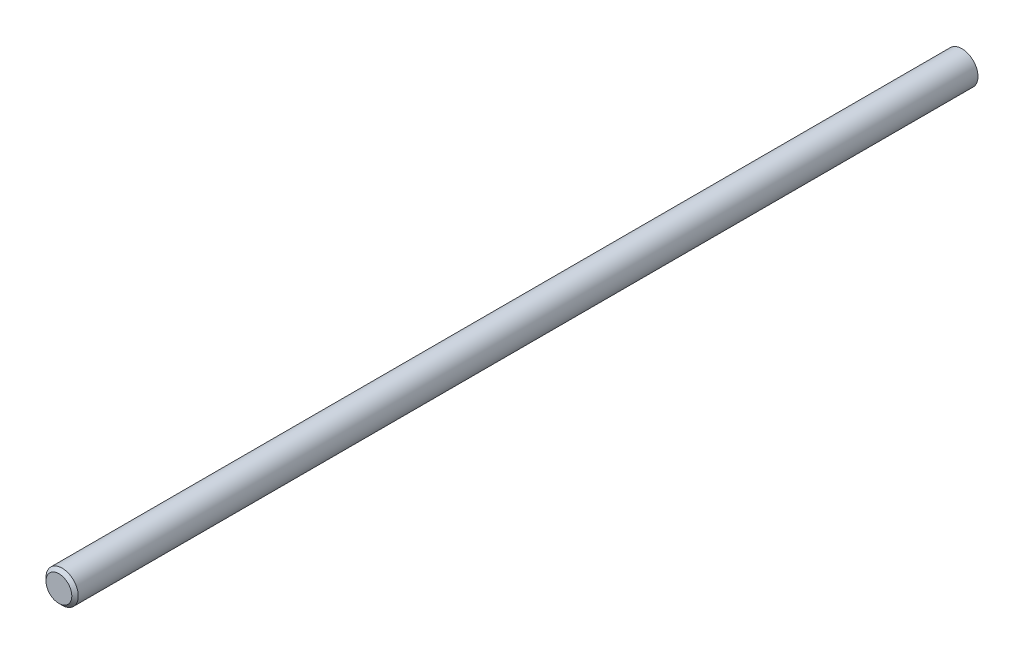
SolidWorks part; units mm, degrees
ref_plane "Front" through (0, 0, 0) normal (0, 0, 1) x (1, 0, 0)
ref_plane "Top" through (0, 0, 0) normal (0, 1, 0) x (1, 0, 0)
ref_plane "Right" through (0, 0, 0) normal (1, 0, 0) x (0, 0, -1)
sketch "Esquisse1" plane through (0, 0, 0) normal (0, 0, 1) x (1, 0, 0)
  circle A0 centre (0, 0) radius 5
  dimension "D1" = 10
extrude "Boss.-Extru.1" add sketch "Esquisse1" along normal blind 280
chamfer "Chanfrein1" distance 1 angle 45 1 edges at (5, 0, 280)
